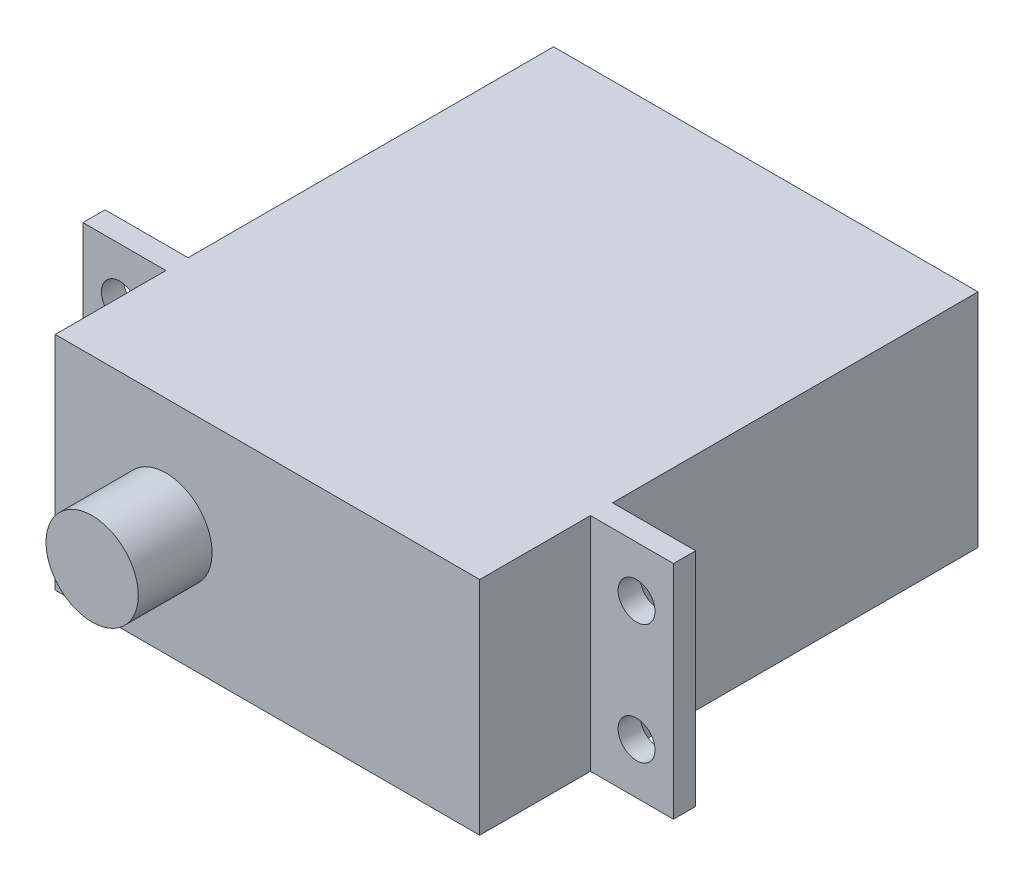
SolidWorks part; units mm, degrees
ref_plane "前视基准面" through (0, 0, 0) normal (0, 0, 1) x (1, 0, 0)
ref_plane "上视基准面" through (0, 0, 0) normal (0, 1, 0) x (1, 0, 0)
ref_plane "右视基准面" through (0, 0, 0) normal (1, 0, 0) x (0, 0, -1)
sketch "草图2" plane through (0, 0, 0) normal (0, 0, 1) x (1, 0, 0)
  line L1 (-11.5, -6) -> (11.5, -6)
  line L2 (-11.5, -6) -> (-11.5, 6)
  line L3 (-11.5, 6) -> (11.5, 6)
  line L4 (11.5, -6) -> (11.5, 6)
  line L5 (-11.5, -6) -> (11.5, 6) construction
  line L6 (-11.5, 6) -> (11.5, -6) construction
  point P0 (0, 0)
  dimension "D1" = 23
  dimension "D2" = 12
extrude "凸台-拉伸1" add sketch "草图2" along normal blind 27
sketch "草图3" plane through (0, 0, 27) normal (0, 0, 1) x (1, 0, 0)
  line L0 (-11.5, -6) -> (11.5, -6) construction
  line L1 (-16, 6) -> (16, 6)
  line L2 (-16, 6) -> (-16, -6)
  line L3 (-16, -6) -> (16, -6)
  line L4 (16, 6) -> (16, -6)
  line L5 (-16, 6) -> (16, -6) construction
  line L6 (-16, -6) -> (16, 6) construction
  point P0 (0, 0)
  dimension "D1" = 32
extrude "凸台-拉伸2" add sketch "草图3" against normal blind 1.2 from offset 6 offset against normal yes
sketch "草图4" plane through (0, 0, 27) normal (0, 0, 1) x (1, 0, 0)
  line L0 (-11.5, 6) -> (-11.5, -6) construction
  circle A0 centre (-5.5, 0) radius 2.5
  dimension "D1" = 5
  dimension "D2" = 6
extrude "凸台-拉伸3" add sketch "草图4" along normal blind 4
sketch "草图5" plane through (0, 0, 21) normal (0, 0, 1) x (1, 0, 0)
  line L0 (0, 0) -> (18.4639, 0) construction
  line L1 (0, 0) -> (0, 8.0078) construction
  line L4 (16, -6) -> (16, 6) construction
  circle A0 centre (14, 3.25) radius 1
  circle A1 centre (14, -3.25) radius 1
  circle A2 centre (-14, -3.25) radius 1
  circle A3 centre (-14, 3.25) radius 1
  dimension "D1" = 2
  dimension "D2" = 1
  dimension "D3" = 4.5
extrude "切除-拉伸1" cut sketch "草图5" against normal blind 4
